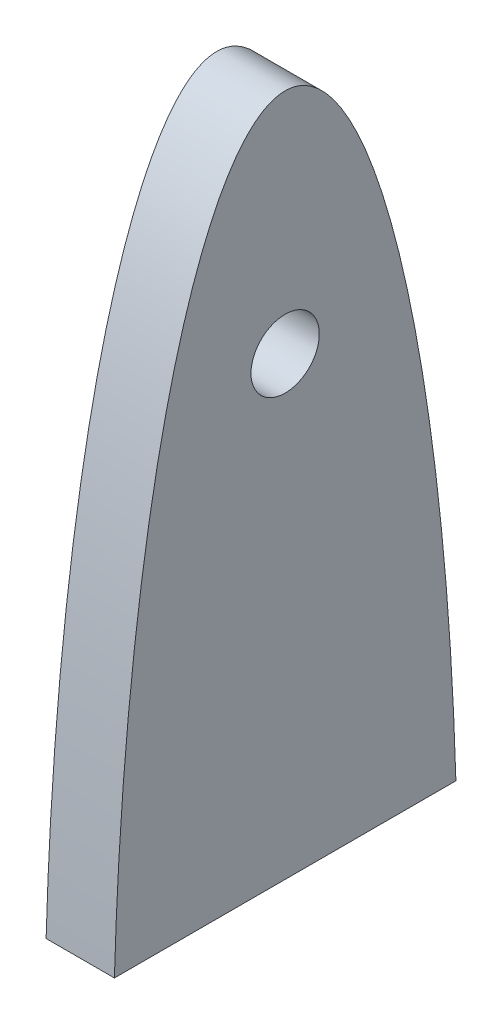
SolidWorks part; units mm, degrees
ref_plane "Front Plane" through (0, 0, 0) normal (0, 0, 1) x (1, 0, 0)
ref_plane "Top Plane" through (0, 0, 0) normal (0, 1, 0) x (1, 0, 0)
ref_plane "Right Plane" through (0, 0, 0) normal (1, 0, 0) x (0, 0, -1)
ref_plane "Plane1" through (3, 0, 0) normal (1, 0, 0) x (0, 0, -1)
sketch "Sketch1" plane through (3, 0, 0) normal (1, 0, 0) x (0, 0, -1)
  line L0 (-7.5, 0) -> (7.5, 0)
  circle A0 centre (0, 20) radius 1.5
  ellipse E0 centre (0, -4.7368) end of major axis (0, 30) minor radius 7.5707 (7.5, 0) -> (-7.5, 0) ccw
  point P0 (0, -4.7368)
  point P1 (7.5707, -4.7368)
  point P2 (0, 30)
  point P3 (7.5, 0)
  point P4 (-7.5, 0)
  point P5 (0, 30)
  point P6 (0, -39.4737)
extrude "Boss-Extrude1" add sketch "Sketch1" against normal blind 3
